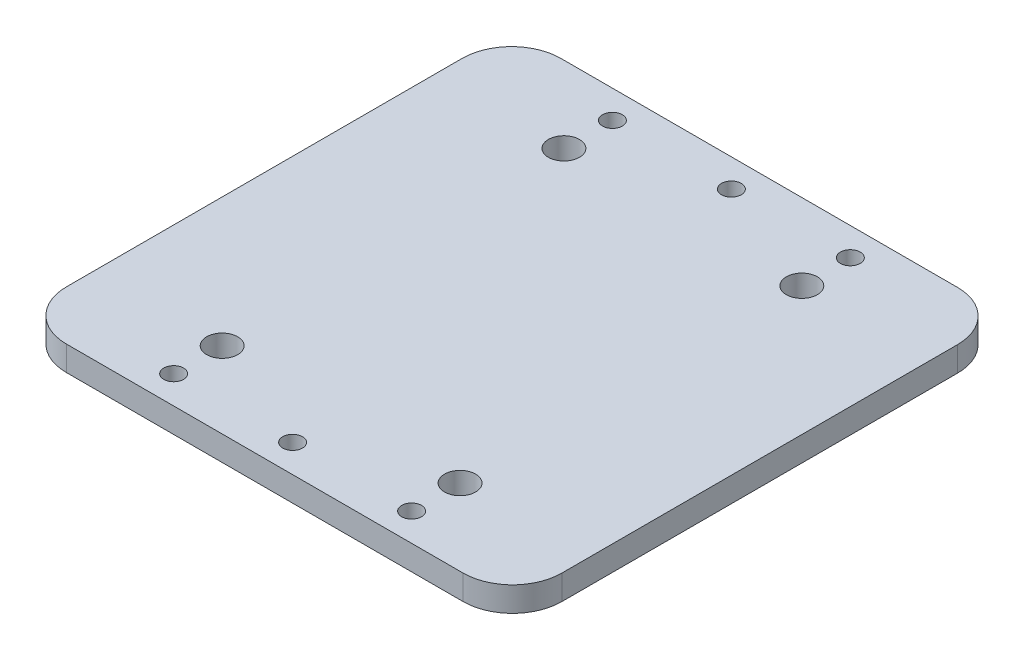
SolidWorks part; units mm, degrees
ref_plane "前视基准面" through (0, 0, 0) normal (0, 0, 1) x (1, 0, 0)
ref_plane "上视基准面" through (0, 0, 0) normal (0, 1, 0) x (1, 0, 0)
ref_plane "右视基准面" through (0, 0, 0) normal (1, 0, 0) x (0, 0, -1)
sketch "草图1" plane through (0, 0, 0) normal (0, 1, 0) x (1, 0, 0)
  line L0 (4.4021, 70.7575) -> (4.4021, -29.2425) construction
  line L1 (-45.6979, 70.7575) -> (54.5021, 70.7575)
  line L2 (-45.6979, 70.7575) -> (-45.6979, -29.2425)
  line L3 (-45.6979, -29.2425) -> (54.5021, -29.2425)
  line L4 (54.5021, 70.7575) -> (54.5021, -29.2425)
  line L5 (-45.6979, 20.7575) -> (54.5021, 20.7575) construction
  circle A0 centre (-19.6479, 55.3075) radius 3.14
  circle A1 centre (28.4521, 55.3075) radius 3.14
  circle A2 centre (28.4521, -13.7925) radius 3.14
  circle A3 centre (-19.6479, -13.7925) radius 3.14
  circle A4 centre (-19.6479, 65.11) radius 2
  circle A5 centre (4.4021, 65.11) radius 2
  circle A6 centre (28.4521, 65.11) radius 2
  circle A7 centre (28.4521, -23.595) radius 2
  circle A8 centre (4.4021, -23.595) radius 2
  circle A9 centre (-19.6479, -23.595) radius 2
  dimension "D3" = 6.28
  dimension "D8" = 4
  dimension "D9" = 4
  dimension "D10" = 4
  dimension "D1" = 100.2
  dimension "D2" = 100
  dimension "D4" = 26.05
  dimension "D5" = 15.45
  dimension "D6" = 2
  dimension "D7" = 2
extrude "凸台-拉伸1" add sketch "草图1" along normal blind 5
fillet "圆角1" radius 10 4 edges at (-45.6979, 2.5, -70.7575) (54.5021, 2.5, -70.7575) (-45.6979, 2.5, 29.2425) (54.5021, 2.5, 29.2425)
